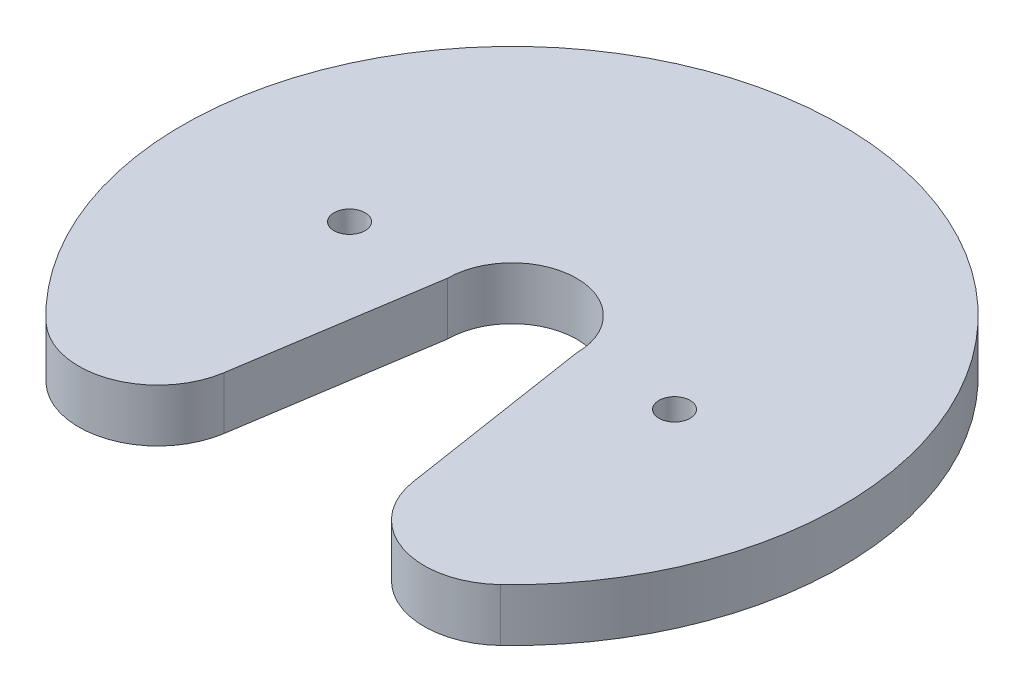
SolidWorks part; units mm, degrees
ref_plane "Front Plane" through (0, 0, 0) normal (0, 0, 1) x (1, 0, 0)
ref_plane "Top Plane" through (0, 0, 0) normal (0, 1, 0) x (1, 0, 0)
ref_plane "Right Plane" through (0, 0, 0) normal (1, 0, 0) x (0, 0, -1)
sketch "Sketch1" plane through (0, 0, 0) normal (0, 1, 0) x (1, 0, 0)
  line L0 (6.223, 0) -> (9.1065, -18.6424)
  line L1 (0, -6.223) -> (0, -10.1281) construction
  line L2 (-6.223, 0) -> (-9.1065, -18.6424)
  arc A0 (21.8908, -22.9969) -> (-21.8908, -22.9969) centre (0, 0) ccw
  arc A1 (6.223, 0) -> (-6.223, 0) centre (0, 0) ccw
  arc A2 (9.1065, -18.6424) -> (21.8908, -22.9969) centre (16.637, -17.4776) ccw
  arc A3 (-9.1065, -18.6424) -> (-21.8908, -22.9969) centre (-16.637, -17.4776) cw
  circle A4 centre (15.651, 0) radius 1.5
  circle A5 centre (-15.651, 0) radius 1.5
  point P10 (10.8389, -29.8426)
  point P13 (-10.8389, -29.8426)
  dimension "D1" = 63.5
  dimension "D2" = 12.446
  dimension "D3" = 7.62
  dimension "D4" = 3
extrude "Boss-Extrude1" add sketch "Sketch1" along normal blind 5.08
